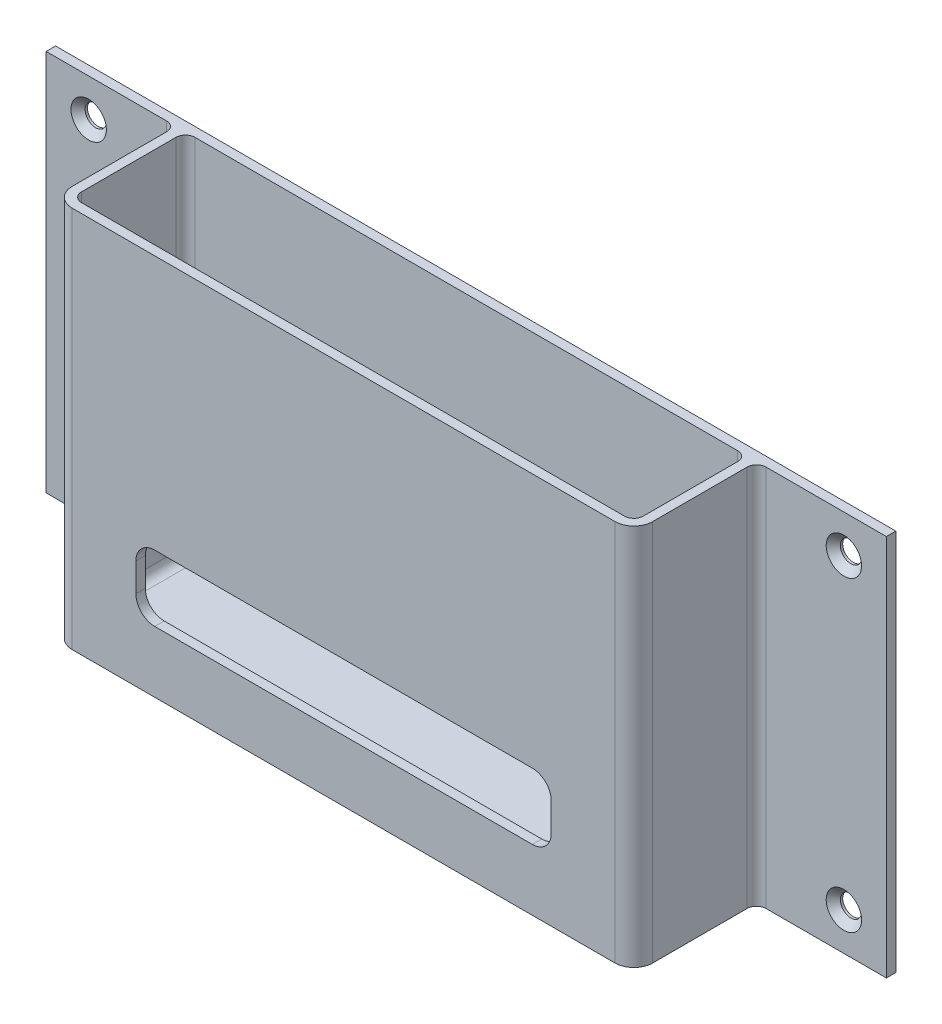
SolidWorks part; units mm, degrees
ref_plane "Front Plane" through (0, 0, 0) normal (0, 0, 1) x (1, 0, 0)
ref_plane "Top Plane" through (0, 0, 0) normal (0, 1, 0) x (1, 0, 0)
ref_plane "Right Plane" through (0, 0, 0) normal (1, 0, 0) x (0, 0, -1)
sketch "Sketch2" plane through (0, 0, 0) normal (0, 1, 0) x (1, 0, 0)
  line L0 (89, 0) -> (-89, 0)
  line L1 (-89, 0) -> (-89, -2)
  line L2 (-89, -2) -> (-63.5, -2)
  line L3 (-61.5, -4) -> (-61.5, -24)
  line L4 (-57.5, -28) -> (57.5, -28)
  line L5 (61.5, -24) -> (61.5, -4)
  line L6 (63.5, -2) -> (89, -2)
  line L7 (89, -2) -> (89, 0)
  line L8 (57.5, -2) -> (-57.5, -2)
  line L9 (-59.5, -4) -> (-59.5, -24)
  line L10 (-57.5, -26) -> (57.5, -26)
  line L11 (59.5, -24) -> (59.5, -4)
  line L12 (-59.5, -6.1481) -> (-61.5, -6.1481) construction
  line L13 (-20.9815, -26) -> (-20.9815, -28) construction
  line L14 (59.5, -6.1481) -> (61.5, -6.1481) construction
  line L15 (0, -2) -> (0, 0) construction
  arc A0 (57.5, -26) -> (59.5, -24) centre (57.5, -24) ccw
  arc A1 (57.5, -2) -> (59.5, -4) centre (57.5, -4) cw
  arc A2 (-57.5, -2) -> (-59.5, -4) centre (-57.5, -4) ccw
  arc A3 (-59.5, -24) -> (-57.5, -26) centre (-57.5, -24) ccw
  arc A4 (57.5, -28) -> (61.5, -24) centre (57.5, -24) ccw
  arc A5 (-61.5, -24) -> (-57.5, -28) centre (-57.5, -24) ccw
  arc A6 (61.5, -4) -> (63.5, -2) centre (63.5, -4) cw
  arc A7 (-63.5, -2) -> (-61.5, -4) centre (-63.5, -4) cw
  point P4 (0, 0)
  point P23 (68.6408, 0)
  point P28 (59.5, -2)
  point P31 (-59.5, -2)
  point P40 (61.5, -2)
  point P43 (-61.5, -2)
  point P44 (0, 0)
  dimension "D6" = 2
  dimension "D7" = 4
  dimension "D8" = 2
  dimension "D1" = 2
  dimension "D2" = 2
  dimension "D3" = 119
  dimension "D4" = 178
  dimension "D5" = 24
extrude "Boss-Extrude1" add sketch "Sketch2" along normal blind 78
sketch "Sketch3" plane through (0, 0, 0) normal (0, -1, 0) x (1, 0, 0)
  line L8 (-89, 2) -> (-89, 0)
  line L9 (-89, 0) -> (89, 0)
  line L10 (89, 0) -> (89, 2)
  line L11 (89, 2) -> (63.5, 2)
  line L12 (61.5, 4) -> (61.5, 24)
  line L13 (57.5, 28) -> (-57.5, 28)
  line L14 (-61.5, 24) -> (-61.5, 4)
  line L15 (-63.5, 2) -> (-89, 2)
  line L16 (-89, 2) -> (-89, 0)
  line L17 (-89, 0) -> (89, 0)
  line L18 (89, 0) -> (89, 2)
  line L19 (89, 2) -> (63.5, 2)
  line L20 (61.5, 4) -> (61.5, 24)
  line L21 (57.5, 28) -> (-57.5, 28)
  line L22 (-61.5, 24) -> (-61.5, 4)
  line L23 (-63.5, 2) -> (-89, 2)
  arc A4 (61.5, 4) -> (63.5, 2) centre (63.5, 4) ccw
  arc A5 (61.5, 24) -> (57.5, 28) centre (57.5, 24) ccw
  arc A6 (-57.5, 28) -> (-61.5, 24) centre (-57.5, 24) ccw
  arc A7 (-63.5, 2) -> (-61.5, 4) centre (-63.5, 4) ccw
  arc A8 (61.5, 4) -> (63.5, 2) centre (63.5, 4) ccw
  arc A9 (61.5, 24) -> (57.5, 28) centre (57.5, 24) ccw
  arc A10 (-57.5, 28) -> (-61.5, 24) centre (-57.5, 24) ccw
  arc A11 (-63.5, 2) -> (-61.5, 4) centre (-63.5, 4) ccw
  dimension "D1" = 0
extrude "Boss-Extrude2" add sketch "Sketch3" along normal blind 3
sketch "Sketch4" plane through (0, 0, 28) normal (0, 0, 1) x (1, 0, 0)
  line L0 (57.5, 0) -> (-57.5, 0) construction
  line L1 (57.5, 0) -> (-57.5, 0) construction
  line L2 (0, 0) -> (0, 10) construction
  line L4 (-40, 24) -> (40, 24)
  line L5 (-44, 20) -> (-44, 14)
  line L6 (-40, 10) -> (40, 10)
  line L7 (44, 20) -> (44, 14)
  line L8 (-44, 24) -> (44, 10) construction
  line L9 (-44, 10) -> (44, 24) construction
  arc A0 (40, 24) -> (44, 20) centre (40, 20) cw
  arc A1 (40, 10) -> (44, 14) centre (40, 14) ccw
  arc A2 (-44, 14) -> (-40, 10) centre (-40, 14) ccw
  arc A3 (-40, 24) -> (-44, 20) centre (-40, 20) ccw
  point P4 (0, 17)
  point P9 (0, 10)
  point P10 (0, 0)
  dimension "D4" = 4
  dimension "D1" = 10
  dimension "D2" = 14
  dimension "D3" = 88
extrude "Cut-Extrude1" cut sketch "Sketch4" against normal up to surface (2 mm away) up to face at (0, 39, 26)
fillet "Fillet1" radius 2 8 edges at (-59.5, 0, 14) (-58.9142, 0, 2.5858) (0, 0, 2) (58.9142, 0, 2.5858) (59.5, 0, 14) (58.9142, 0, 25.4142) (0, 0, 26) (-58.9142, 0, 25.4142)
sketch "Sketch5" plane through (0, 0, 2) normal (0, 0, 1) x (1, 0, 0)
  line L0 (-80, 78) -> (-80, -3) construction
  line L1 (-89, 78) -> (-63.5, 78) construction
  line L2 (-63.5, -3) -> (-89, -3) construction
  line L3 (80, 78) -> (80, -3) construction
  line L6 (-80, 5) -> (80, 5) construction
  line L7 (-80, 70) -> (80, 70) construction
  line L8 (89, -3) -> (63.5, -3) construction
  line L9 (63.5, 78) -> (89, 78) construction
  line L10 (0, 70) -> (0, 78) construction
  line L11 (-57.5, 78) -> (57.5, 78) construction
  circle A0 centre (-80, 70) radius 2.25
  circle A1 centre (-80, 5) radius 2.25
  circle A2 centre (80, 5) radius 2.25
  circle A3 centre (80, 70) radius 2.25
  dimension "D3" = 4.5
  dimension "D1" = 8
  dimension "D2" = 8
  dimension "D4" = 160
extrude "Cut-Extrude2" cut sketch "Sketch5" against normal through all
chamfer "Chamfer1" distance 1.5 angle 45 4 edges at (82.25, 70, 2) (82.25, 5, 2) (-77.75, 5, 2) (-77.75, 70, 2)
